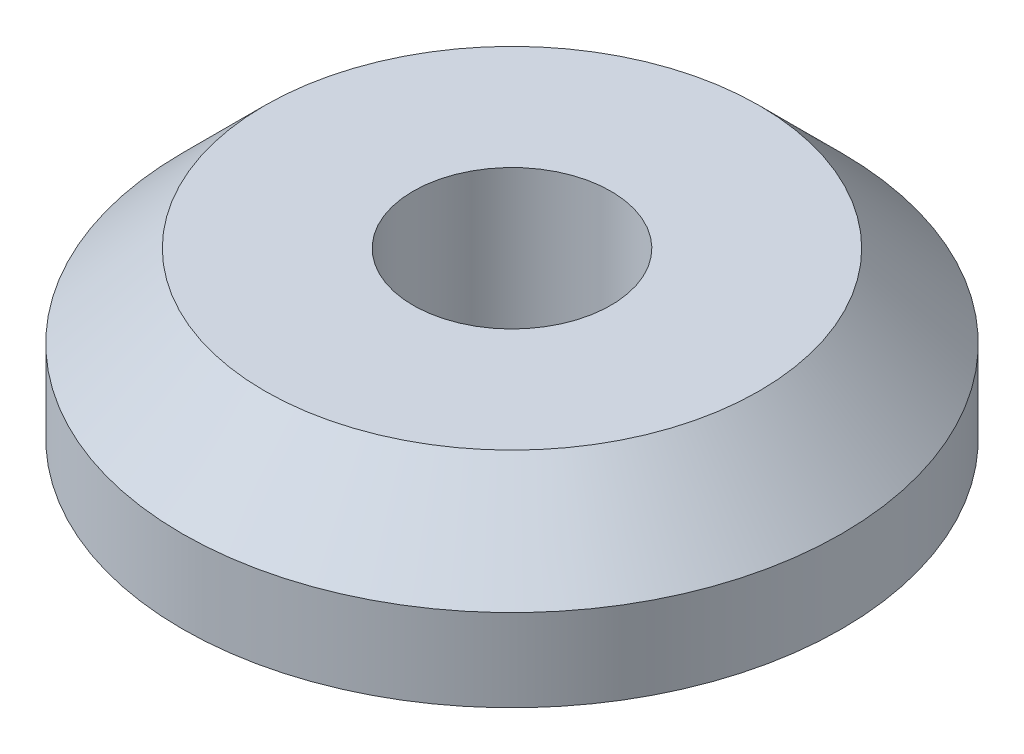
SolidWorks part; units mm, degrees
material "Alumina"
ref_plane "Front Plane" through (0, 0, 0) normal (0, 0, 1) x (1, 0, 0)
ref_plane "Top Plane" through (0, 0, 0) normal (0, 1, 0) x (1, 0, 0)
ref_plane "Right Plane" through (0, 0, 0) normal (1, 0, 0) x (0, 0, -1)
sketch "Sketch1" plane through (0, 0, 0) normal (0, 0, 1) x (1, 0, 0)
  line L0 (-1.905, 0) -> (-1.905, -4.7498)
  line L1 (-1.905, -4.7498) -> (-3.5687, -4.7498)
  line L2 (-3.5687, -4.7498) -> (-3.5687, -3.175)
  line L3 (-3.5687, -3.175) -> (-6.35, -3.175)
  line L4 (-6.35, -3.175) -> (-6.35, -1.5875)
  line L5 (-6.35, -1.5875) -> (-4.7625, 0)
  line L6 (-4.7625, 0) -> (-1.905, 0)
  line L7 (0, 0) -> (0, -4.7498) construction
  dimension "D" = 3.81
  dimension "A" = 12.7
  dimension "C" = 7.1374
  dimension "LG" = 1.5748
  dimension "D6" = 45
  dimension "B" = 3.175
  dimension "D7" = 1.5875
revolve "Revolve1" add sketch "Sketch1" angle 360 about L7
equation "\"D7@Sketch1\" = \"B@Sketch1\"/2"
